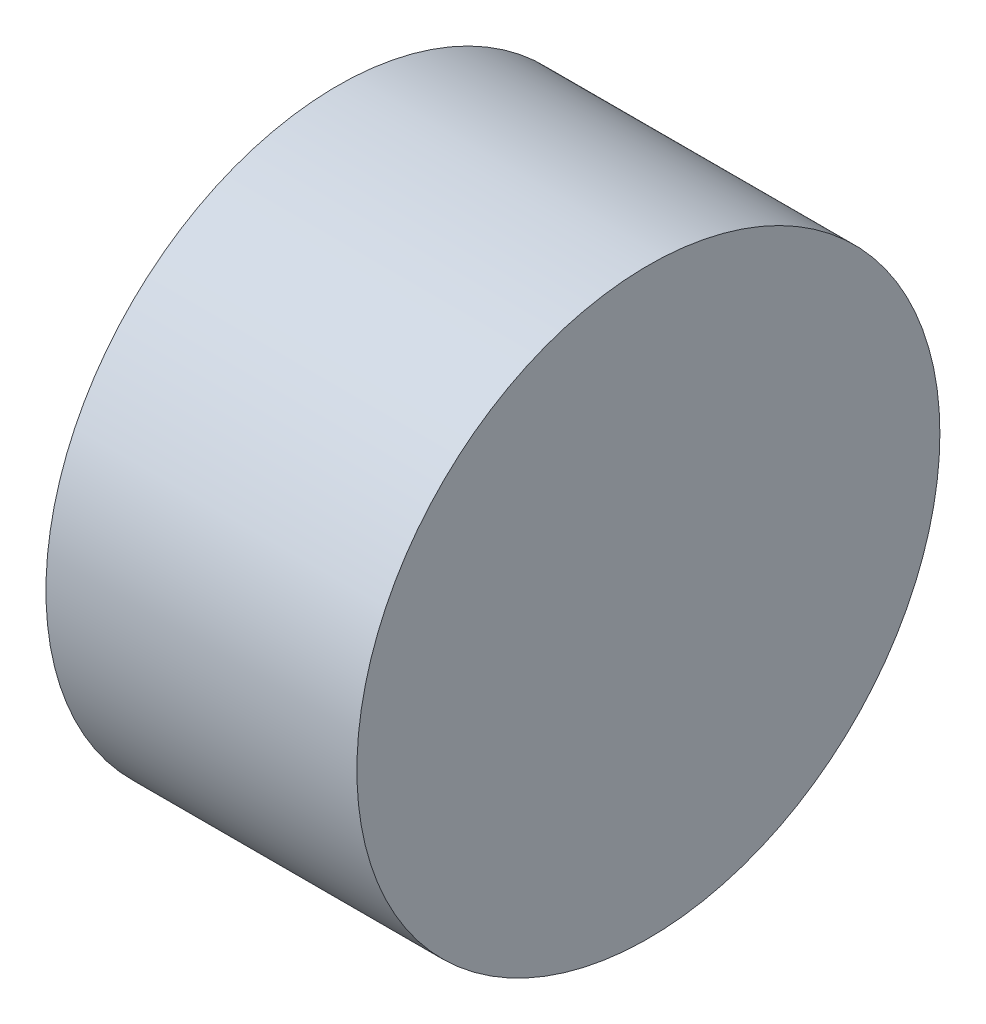
SolidWorks part; units mm, degrees
ref_plane "Front Plane" through (0, 0, 0) normal (0, 0, 1) x (1, 0, 0)
ref_plane "Top Plane" through (0, 0, 0) normal (0, 1, 0) x (1, 0, 0)
ref_plane "Right Plane" through (0, 0, 0) normal (1, 0, 0) x (0, 0, -1)
sketch "Sketch1" plane through (-28.928, 0, 0) normal (1, 0, 0) x (0, 0, -1)
  circle A1 centre (-285.214, 803.4676) radius 11.45 construction
  circle A2 centre (-285.214, 803.4676) radius 11.25
  dimension "D1" = 22.5
extrude "Boss-Extrude1" add sketch "Sketch1" along normal blind 12
